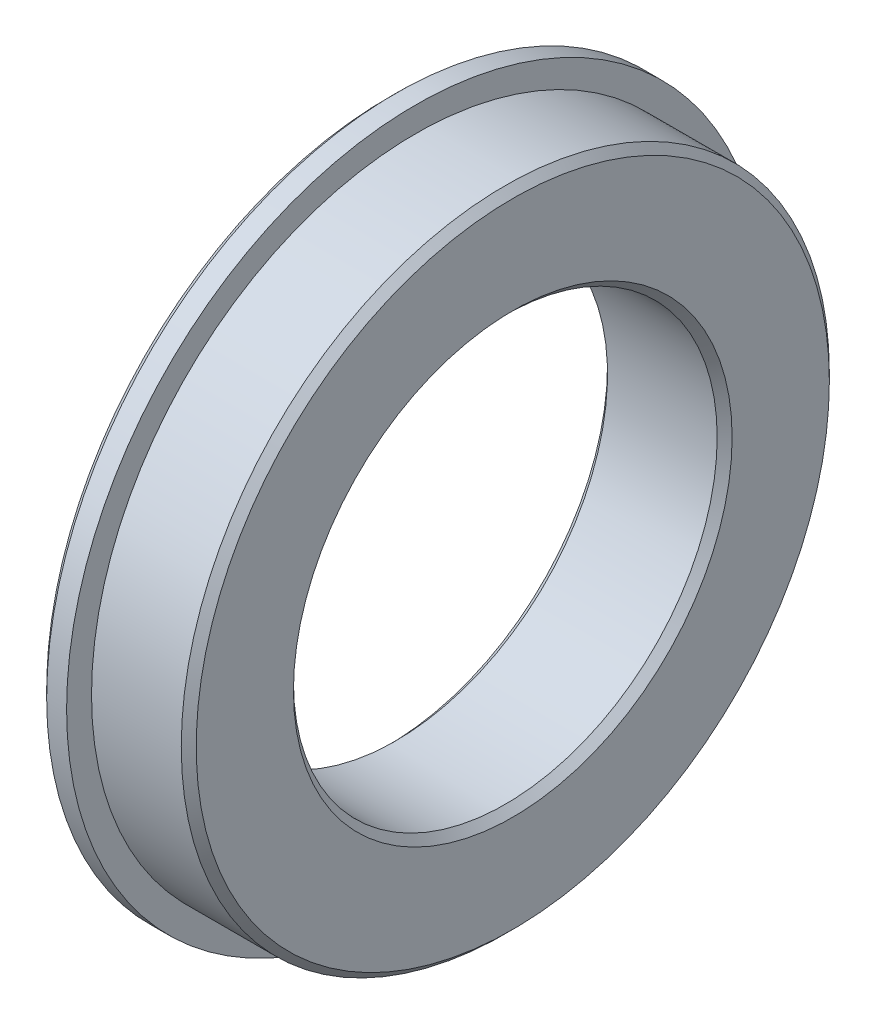
SolidWorks part; units mm, degrees
material "镍"
ref_plane "前视基准面" through (0, 0, 0) normal (0, 0, 1) x (1, 0, 0)
ref_plane "上视基准面" through (0, 0, 0) normal (0, 1, 0) x (1, 0, 0)
ref_plane "右视基准面" through (0, 0, 0) normal (1, 0, 0) x (0, 0, -1)
sketch "草图1" plane through (0, 0, 0) normal (1, 0, 0) x (0, 0, -1)
  circle A0 centre (0, 0) radius 8.5
  circle A1 centre (0, 0) radius 14
  dimension "D1" = 17
  dimension "D2" = 28
extrude "凸台-拉伸1" add sketch "草图1" along normal blind 5
sketch "草图2" plane through (5, 0, 0) normal (1, 0, 0) x (0, 0, -1)
  circle A0 centre (0, 0) radius 13
  circle A1 centre (0, 0) radius 16.1272
  dimension "D1" = 26
extrude "切除-拉伸1" cut sketch "草图2" against normal blind 3.9
chamfer "倒角1" distance 0.3 angle 45 4 edges at (5, 0, -13) (0, 0, -14) (5, 0, -8.5) (0, 0, -8.5)
